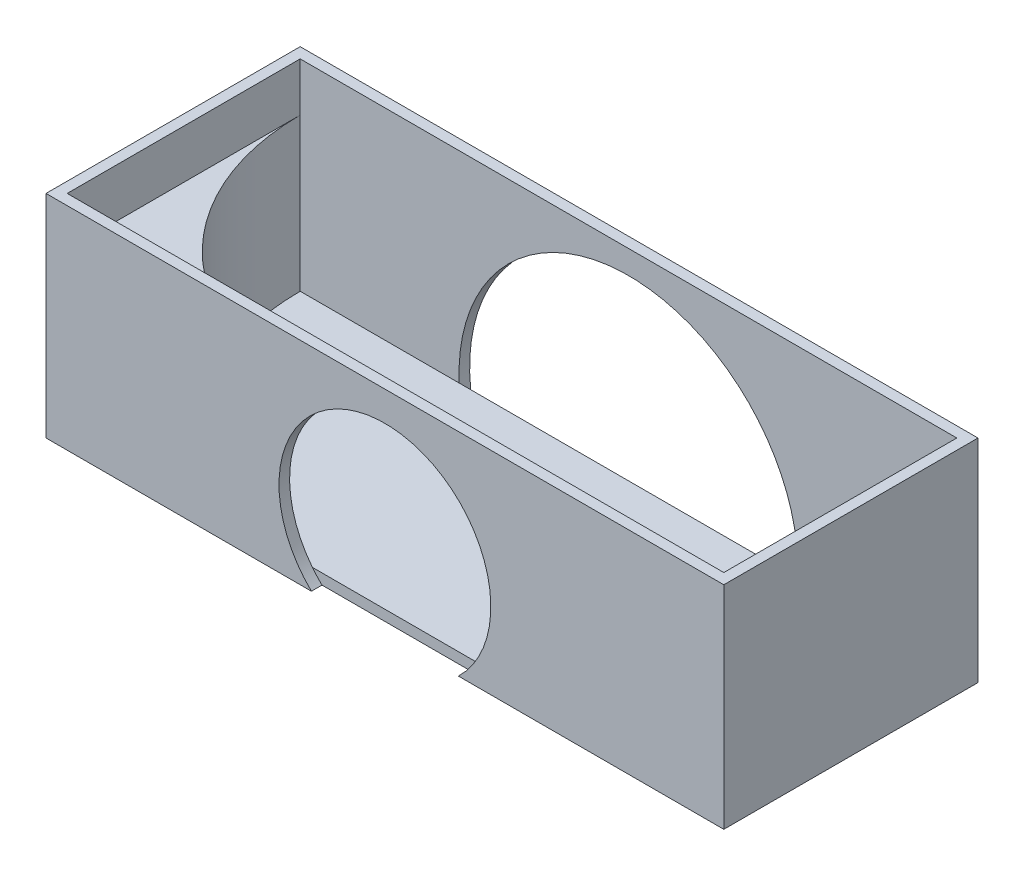
SolidWorks part; units mm, degrees
ref_plane "Front Plane" through (0, 0, 0) normal (0, 0, 1) x (1, 0, 0)
ref_plane "Top Plane" through (0, 0, 0) normal (0, 1, 0) x (1, 0, 0)
ref_plane "Right Plane" through (0, 0, 0) normal (1, 0, 0) x (0, 0, -1)
sketch "Sketch1" plane through (0, 0, 0) normal (0, 1, 0) x (1, 0, 0)
  line L1 (101.6, -38.1) -> (-101.6, -38.1)
  line L2 (101.6, -38.1) -> (101.6, 38.1)
  line L3 (101.6, 38.1) -> (-101.6, 38.1)
  line L4 (-101.6, -38.1) -> (-101.6, 38.1)
  line L5 (101.6, -38.1) -> (-101.6, 38.1) construction
  line L6 (101.6, 38.1) -> (-101.6, -38.1) construction
  point P0 (0, 0)
  dimension "D1" = 203.2
  dimension "D2" = 76.2
extrude "Boss-Extrude1" add sketch "Sketch1" along normal blind 63.5
shell "Shell1" thickness 3.175
sketch "Sketch2" plane through (0, 0, -38.1) normal (0, 0, -1) x (-1, 0, 0)
  line L1 (-101.6, 0) -> (101.6, 0) construction
  line L2 (-50.4822, 0) -> (50.4822, 0)
  arc A0 (-50.4822, 0) -> (50.4822, 0) centre (0, 5.6735) cw
  point P3 (0, 56.4735)
  dimension "D1" = 50.8
  dimension "D2" = 50.4822
  dimension "D3" = 0
extrude "Cut-Extrude1 BACK MOUSEHOLE" cut sketch "Sketch2" against normal up to surface (3.175 mm away) up to face at (0, 33.3375, -34.925)
sketch "Sketch3" plane through (0, 0, 38.1) normal (0, 0, 1) x (1, 0, 0)
  circle A0 centre (0, 22.86) radius 31.75
  dimension "D1" = 63.5
  dimension "D2" = 22.86
extrude "Cut-Extrude2" cut sketch "Sketch3" against normal up to surface (3.175 mm away) up to face at (0, 33.3375, 34.925)
sketch "Sketch4" plane through (0, 3.175, 0) normal (0, 1, 0) x (1, 0, 0)
  line L0 (-98.425, 34.925) -> (-98.425, -34.925)
  line L1 (-98.425, -34.925) -> (-39.5001, -34.925)
  line L2 (-98.425, -34.925) -> (98.425, -34.925) construction
  arc A0 (-98.425, 34.925) -> (-39.5001, -34.925) centre (-27.5622, 34.925) ccw
extrude "Boss-Extrude2" add sketch "Sketch4" along normal blind 45.72 separate body
equation "\"eighthinch\"= 0.125"
